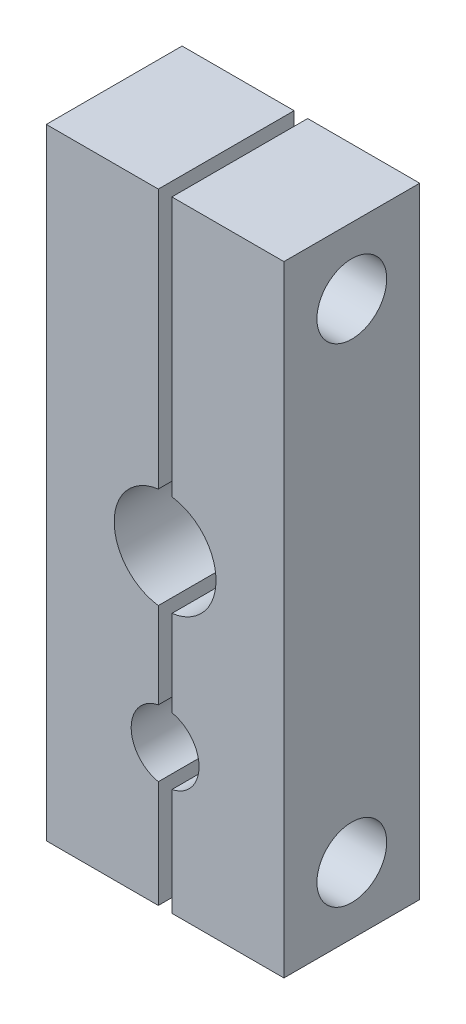
SolidWorks part; units mm, degrees
ref_plane "Front Plane" through (0, 0, 0) normal (0, 0, 1) x (1, 0, 0)
ref_plane "Top Plane" through (0, 0, 0) normal (0, 1, 0) x (1, 0, 0)
ref_plane "Right Plane" through (0, 0, 0) normal (1, 0, 0) x (0, 0, -1)
sketch "Sketch1" plane through (0, 0, 0) normal (0, 0, 1) x (1, 0, 0)
  line L0 (0, 0) -> (0, -15.875) construction
  line L1 (-11.1125, -29.0137) -> (11.1125, -29.0137)
  line L2 (-11.1125, -29.0137) -> (-11.1125, 29.0137)
  line L3 (-11.1125, 29.0137) -> (11.1125, 29.0137)
  line L4 (11.1125, -29.0137) -> (11.1125, 29.0137)
  line L5 (-11.1125, -29.0137) -> (11.1125, 29.0137) construction
  line L6 (-11.1125, 29.0137) -> (11.1125, -29.0137) construction
  circle A0 centre (0, 0) radius 4.7625
  circle A1 centre (0, -15.875) radius 3.175
  point P0 (0, 0)
  dimension "D3" = 9.525
  dimension "D4" = 15.875
  dimension "D5" = 6.35
  dimension "D1" = 22.225
  dimension "D2" = 58.0275
extrude "Boss-Extrude1" add sketch "Sketch1" along normal mid plane 12.7
hole_wizard "1/4 Clearance Hole1" positions "Sketch3" profile "Sketch2" hole size "1/4" standard "ANSI Inch" end condition through all
sketch "Sketch3" plane through (-11.1125, 0, 0) normal (-1, 0, 0) x (0, 0, 1)
  line L0 (0, 22.8203) -> (0, -22.8203) construction
  point P0 (0, 22.8203)
  point P2 (0, -22.8203)
  dimension "D1" = 45.6406
sketch "Sketch2" plane through (-11.1125, 22.8203, 0) normal (0, 1, 0) x (0, 0, 1)
  line L0 (0, 0) -> (0, 22.225)
  line L1 (0, 22.225) -> (3.2639, 22.225)
  line L2 (3.2639, 22.225) -> (3.2639, 0)
  line L5 (3.2639, 0) -> (0, 0)
  line L11 (0, -6.35) -> (0, 107.95) construction
  dimension "Thru Hole Dia." = 6.5278
  dimension "Thru Hole Depth" = 22.225
sketch "Sketch4" plane through (0, 0, 0) normal (0, 0, 1) x (1, 0, 0)
  line L1 (-0.635, -31.0103) -> (0.635, -31.0103)
  line L2 (-0.635, -31.0103) -> (-0.635, 31.0103)
  line L3 (-0.635, 31.0103) -> (0.635, 31.0103)
  line L4 (0.635, -31.0103) -> (0.635, 31.0103)
  line L5 (-0.635, -31.0103) -> (0.635, 31.0103) construction
  line L6 (-0.635, 31.0103) -> (0.635, -31.0103) construction
  point P0 (0, 0)
  dimension "D1" = 1.27
extrude "Cut-Extrude1" cut sketch "Sketch4" against normal through all both and the other way through all
